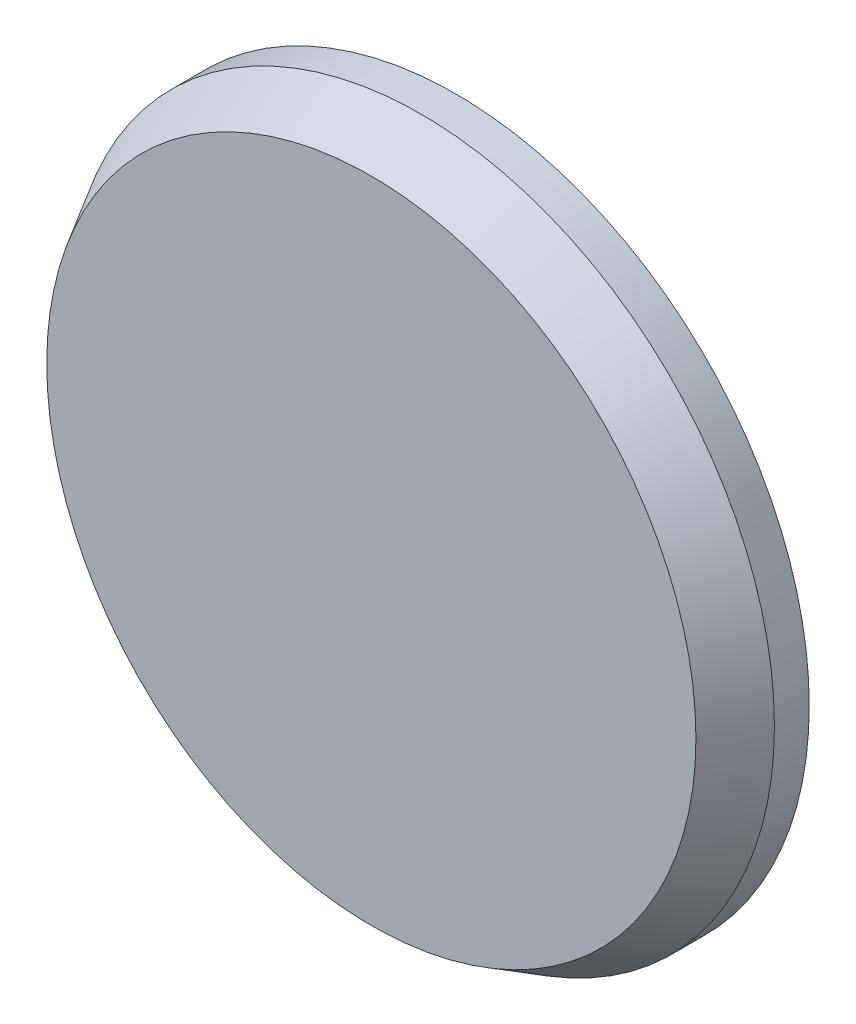
SolidWorks part; units mm, degrees
ref_plane "Přední rovina" through (0, 0, 0) normal (0, 0, 1) x (1, 0, 0)
ref_plane "Horní rovina" through (0, 0, 0) normal (0, 1, 0) x (1, 0, 0)
ref_plane "Pravá rovina" through (0, 0, 0) normal (1, 0, 0) x (0, 0, -1)
sketch "Sketch1" plane through (0, 0, 0) normal (0, 0, 1) x (1, 0, 0)
  circle A0 centre (0, 0) radius 17.75
  dimension "D1" = 35.5
extrude "Boss-Extrude1" add sketch "Sketch1" along normal blind 4.25
sketch "Sketch2" plane through (0, 0, 0) normal (0, 0, -1) x (-1, 0, 0)
  line L9 (14.5045, -1.15) -> (1.15, -1.15)
  line L10 (1.15, -1.15) -> (1.15, -14.5045)
  line L11 (-1.15, -14.5045) -> (-1.15, -1.15)
  line L12 (-1.15, -1.15) -> (-14.5045, -1.15)
  line L13 (-14.5045, 1.15) -> (-1.15, 1.15)
  line L14 (-1.15, 1.15) -> (-1.15, 14.5045)
  line L15 (1.15, 14.5045) -> (1.15, 1.15)
  line L16 (1.15, 1.15) -> (14.5045, 1.15)
  line L17 (-1.15, 14.5045) -> (1.15, 14.5045)
  line L18 (14.5045, 1.15) -> (14.5045, -1.15)
  line L19 (1.15, -14.5045) -> (-1.15, -14.5045)
  line L20 (-14.5045, -1.15) -> (-14.5045, 1.15)
  circle A9 centre (0, 0) radius 14.55
  circle A10 centre (0, 0) radius 17.75 construction
  arc A13 (1.15, -14.5045) -> (14.5045, -1.15) centre (0, 0) ccw
  arc A14 (-14.5045, -1.15) -> (-1.15, -14.5045) centre (0, 0) ccw
  arc A15 (-1.15, 14.5045) -> (-14.5045, 1.15) centre (0, 0) ccw
  arc A16 (14.5045, 1.15) -> (1.15, 14.5045) centre (0, 0) ccw
  dimension "D1" = 14.55
  dimension "D2" = 2.3
  dimension "D3" = 2.3
extrude "Cut-Extrude1" cut sketch "Sketch2" against normal blind 2.75 contours L20 L12 L11 L19 L10 L9 L18 L16 L15 L17 L14 L13
chamfer "Chamfer1" distance 2.5 angle 30 1 edges at (17.75, 0, 4.25)
